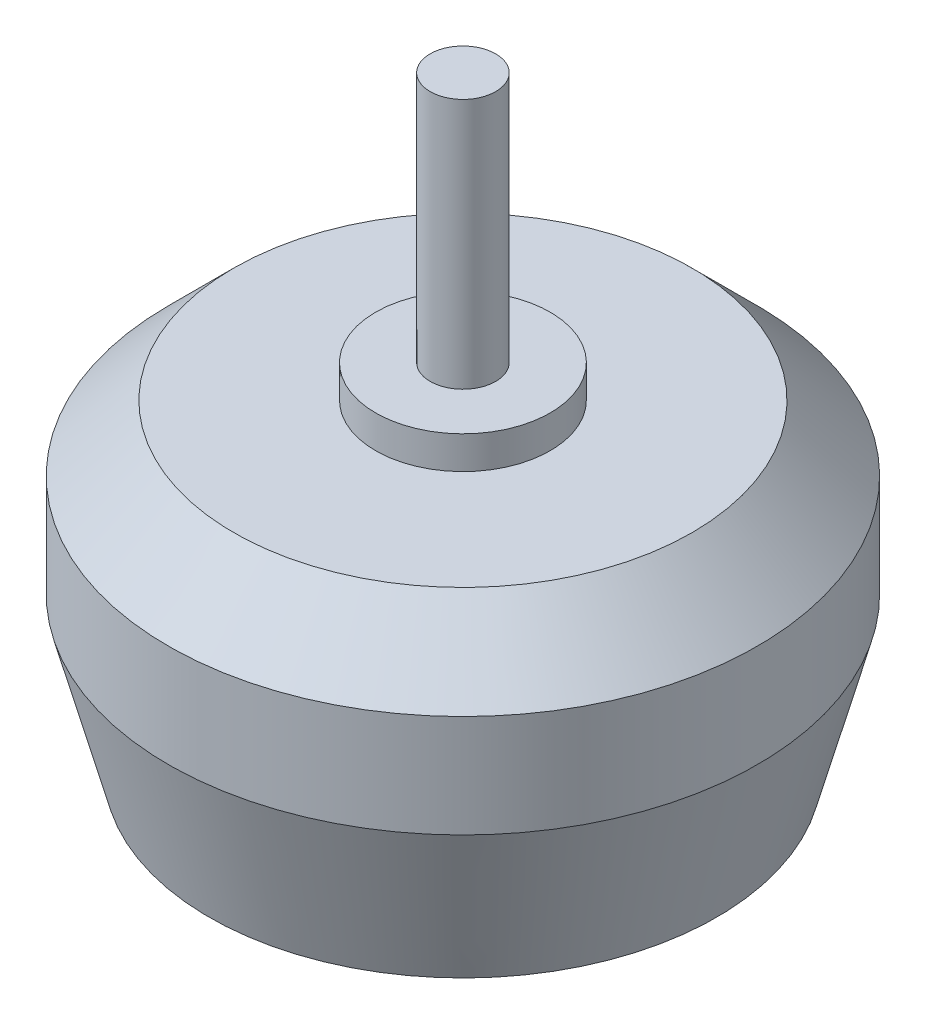
SolidWorks part; units mm, degrees
ref_plane "Front Plane" through (0, 0, 0) normal (0, 0, 1) x (1, 0, 0)
ref_plane "Top Plane" through (0, 0, 0) normal (0, 1, 0) x (1, 0, 0)
ref_plane "Right Plane" through (0, 0, 0) normal (1, 0, 0) x (0, 0, -1)
sketch "Sketch2" plane through (0, 0, 0) normal (0, 0, 1) x (1, 0, 0)
  line L0 (1.5, 0) -> (11.6244, 0)
  line L1 (11.6244, 0) -> (13.5, 7)
  line L2 (13.5, 7) -> (13.5, 11.7)
  line L3 (13.5, 11.7) -> (10.5, 14.7)
  line L4 (10.5, 14.7) -> (4, 14.7)
  line L5 (4, 14.7) -> (4, 16.2)
  line L6 (4, 16.2) -> (1.5, 16.2)
  line L7 (0, 27.7) -> (0, -2.1)
  line L8 (0, -2.1) -> (1.5, -2.1)
  line L9 (1.5, -2.1) -> (1.5, 0)
  line L10 (0, -2.1) -> (0, -17.9238) construction
  line L11 (1.5, 16.2) -> (1.5, 27.7)
  line L12 (1.5, 27.7) -> (0, 27.7)
  dimension "D1" = 27
  dimension "D2" = 3
  dimension "D3" = 2.1
  dimension "D4" = 75
  dimension "D5" = 7
  dimension "D6" = 45
  dimension "D7" = 3
  dimension "D8" = 16.2
  dimension "D9" = 8
  dimension "D10" = 1.5
  dimension "D11" = 27.7
revolve "Revolve1" add sketch "Sketch2" angle 360 about L10
sketch "Sketch3" plane through (0, 0, 0) normal (0, -1, 0) x (1, 0, 0)
  line L0 (0, 9.5) -> (0, -9.5) construction
  line L1 (-8, 0) -> (8, 0) construction
  circle A0 centre (0, 9.5) radius 1.375
  circle A1 centre (0, -9.5) radius 1.375
  circle A2 centre (-8, 0) radius 1.375
  circle A3 centre (8, 0) radius 1.375
  dimension "D3" = 2.75
  dimension "D1" = 19
  dimension "D2" = 16
extrude "Cut-Extrude1" cut sketch "Sketch3" against normal blind 2
